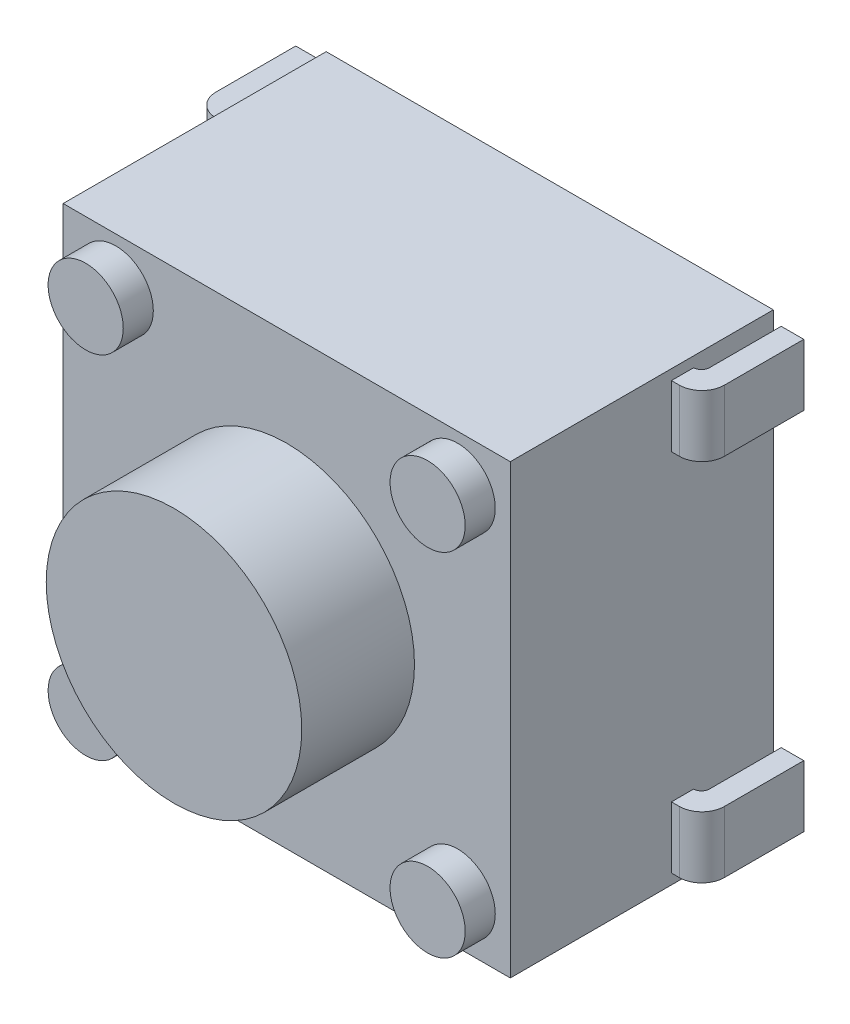
SolidWorks part; units mm, degrees
ref_plane "Alzado" through (0, 0, 0) normal (0, 0, 1) x (1, 0, 0)
ref_plane "Planta" through (0, 0, 0) normal (0, 1, 0) x (1, 0, 0)
ref_plane "Vista lateral" through (0, 0, 0) normal (1, 0, 0) x (0, 0, -1)
sketch "Croquis1" plane through (0, 0, 0) normal (0, 0, 1) x (1, 0, 0)
  line L1 (0, 0) -> (-5.95, 0)
  line L2 (0, 0) -> (0, 5.95)
  line L3 (0, 5.95) -> (-5.95, 5.95)
  line L4 (-5.95, 0) -> (-5.95, 5.95)
extrude "Saliente-Extruir1" add sketch "Croquis1" along normal blind 3.5
sketch "Croquis3" plane through (0, 0, 3.5) normal (0, 0, 1) x (1, 0, 0)
  circle A0 centre (-2.975, 2.975) radius 1.7
extrude "Saliente-Extruir2" add sketch "Croquis3" along normal blind 1.5
sketch "Croquis4" plane through (0, 0, 3.5) normal (0, 0, 1) x (1, 0, 0)
  circle A2 centre (-5.25, 5.3125) radius 0.5
  circle A3 centre (-0.7, 5.3125) radius 0.5
  circle A4 centre (-0.7, 0.6375) radius 0.5
  circle A5 centre (-5.25, 0.6375) radius 0.5
extrude "Saliente-Extruir3" add sketch "Croquis4" along normal blind 0.4
sketch "Croquis5" plane through (0, 0, 0) normal (1, 0, 0) x (0, 0, -1)
  line L1 (0, 0) -> (0, 5.95) construction
  line L2 (0, 5.8125) -> (-1.3558, 5.8125)
  line L3 (0, 5.8125) -> (0, 4.9925)
  line L4 (0, 4.9925) -> (-1.3558, 4.9925)
  line L5 (-1.3558, 5.8125) -> (-1.3558, 4.9925)
  line L6 (-1.3558, 0.1375) -> (-1.3558, 0.9575)
  line L7 (0, 0.9575) -> (-1.3558, 0.9575)
  line L8 (0, 0.1375) -> (0, 0.9575)
  line L9 (0, 0.1375) -> (-1.3558, 0.1375)
extrude "Saliente-Extruir4" add sketch "Croquis5" along normal blind 0.405
fillet "Redondeo1" radius 0.3 1 edges at (0.405, 5.4025, 1.3558)
fillet "Redondeo2" radius 0.3 1 edges at (0.405, 0.5475, 1.3558)
sketch "Croquis9" plane through (-5.95, 0, 0) normal (-1, 0, 0) x (0, 0, 1)
  line L2 (0, 5.95) -> (0, 0) construction
  line L4 (0, 5.8125) -> (1.36, 5.8125)
  line L5 (0, 5.8125) -> (0, 4.9925)
  line L6 (0, 0.1375) -> (1.36, 0.1375)
  line L7 (0, 0.1375) -> (0, 0.9575)
  line L8 (0, 0.9575) -> (1.36, 0.9575)
  line L9 (1.36, 0.1375) -> (1.36, 0.9575)
  line L10 (0, 4.9925) -> (1.36, 4.9925)
  line L11 (1.36, 5.8125) -> (1.36, 4.9925)
  dimension "D1" = 1.36
  dimension "D2" = 0.82
  dimension "D3" = 1.36
  dimension "D4" = 0.82
extrude "Saliente-Extruir5" add sketch "Croquis9" along normal blind 0.405
fillet "Redondeo3" radius 0.3 1 edges at (-6.355, 5.4025, 1.36)
fillet "Redondeo4" radius 0.3 1 edges at (-6.355, 0.5475, 1.36)
sketch "Croquis10" plane through (0, 0.1375, 0) normal (0, -1, 0) x (1, 0, 0)
  line L1 (-5.95, 0) -> (-6.055, 0)
  line L2 (-5.95, 0) -> (-5.95, 1.06)
  line L3 (0.105, 0) -> (0.105, 0.955)
  line L4 (-6.055, 0) -> (-6.055, 0.955)
  line L6 (0, 0) -> (0, 1.06)
  line L7 (0, 0) -> (0.105, 0)
  arc A0 (-5.95, 1.06) -> (-6.055, 0.955) centre (-5.95, 0.955) ccw
  arc A1 (0, 1.06) -> (0.105, 0.955) centre (0, 0.955) cw
extrude "Cortar-Extruir1" cut sketch "Croquis10" against normal through all
